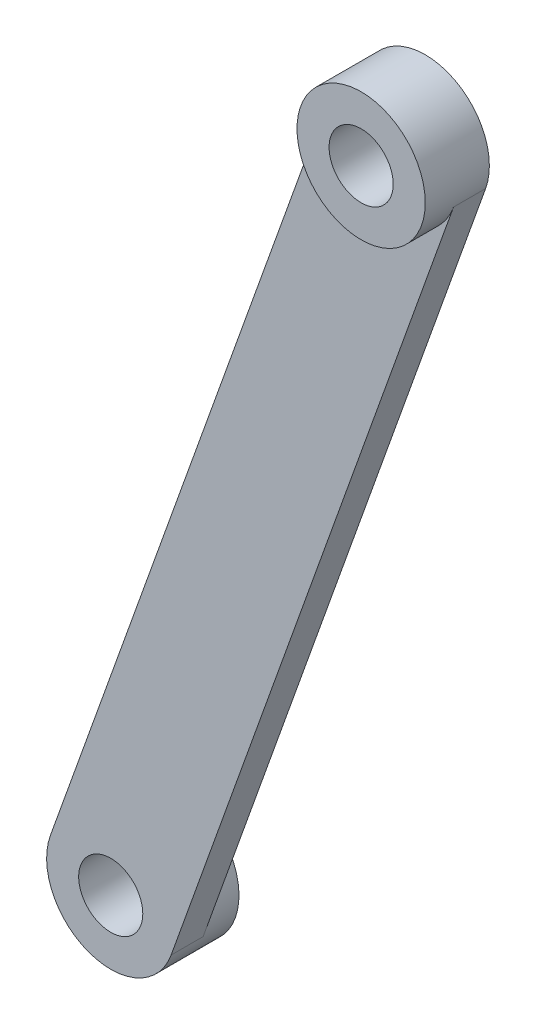
SolidWorks part; units mm, degrees
ref_plane "Front" through (0, 0, 0) normal (0, 0, 1) x (1, 0, 0)
ref_plane "Top" through (0, 0, 0) normal (0, 1, 0) x (1, 0, 0)
ref_plane "Right" through (0, 0, 0) normal (1, 0, 0) x (0, 0, -1)
sketch "Sketch1" plane through (0, 0, 0) normal (0, 0, 1) x (1, 0, 0)
  line L0 (-38, -7.8) -> (-24.0135, 31.2721) construction
  line L1 (-40.9893, -6.73) -> (-27.0028, 32.3421)
  line L2 (-35.0107, -8.87) -> (-21.0243, 30.202)
  arc A0 (-40.9893, -6.73) -> (-35.0107, -8.87) centre (-38, -7.8) ccw
  arc A1 (-21.0243, 30.202) -> (-27.0028, 32.3421) centre (-24.0135, 31.2721) ccw
  circle A2 centre (-24.0135, 31.2721) radius 1.5875
  circle A3 centre (-38, -7.8) radius 1.5875
  point P4 (-31.0068, 11.736)
  dimension "D1" = 3.175
  dimension "D2" = 6.35
extrude "Boss-Extrude1" add sketch "Sketch1" against normal blind 1.5875 from offset 1.5875 offset against normal yes
sketch "Sketch3" plane through (0, 0, -1.5875) normal (0, 0, 1) x (1, 0, 0)
  circle A0 centre (-24.0135, 31.2721) radius 1.5875
  circle A1 centre (-24.0135, 31.2721) radius 3.175
  circle A2 centre (-24.0135, 31.2721) radius 1.5875 construction
  arc A3 (-21.0243, 30.202) -> (-27.0028, 32.3421) centre (-24.0135, 31.2721) ccw construction
extrude "Boss-Extrude2" add sketch "Sketch3" along normal blind 1.5875
sketch "Sketch4" plane through (0, 0, -3.175) normal (0, 0, -1) x (-1, 0, 0)
  circle A0 centre (38, -7.8) radius 1.5875 construction
  arc A1 (35.0107, -8.87) -> (40.9893, -6.73) centre (38, -7.8) ccw construction
  circle A2 centre (38, -7.8) radius 1.5875
  circle A3 centre (38, -7.8) radius 3.175
extrude "Boss-Extrude3" add sketch "Sketch4" along normal blind 1.5875
